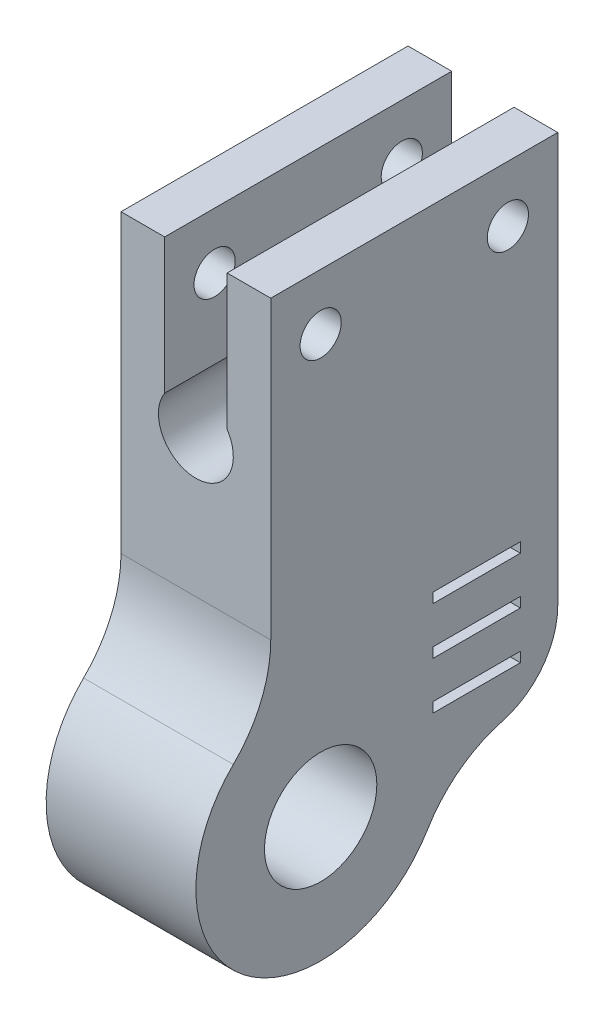
SolidWorks part; units mm, degrees
ref_plane "xy" through (0, 0, 0) normal (0, 0, 1) x (1, 0, 0)
ref_plane "xz" through (0, 0, 0) normal (0, 1, 0) x (1, 0, 0)
ref_plane "yz" through (0, 0, 0) normal (1, 0, 0) x (0, 0, -1)
sketch "Skizze1" plane through (0, 0, 0) normal (1, 0, 0) x (0, 0, -1)
  line L0 (4, 33.8) -> (19, 33.8) construction
  line L1 (13.9955, 0) -> (23, 0)
  line L2 (0, 9.4652) -> (0, 38.3)
  line L3 (0, 38.3) -> (23, 38.3)
  line L4 (23, 0) -> (23, 38.3)
  line L5 (13, 3.8) -> (20, 3.8)
  line L6 (13, 3.8) -> (13, 3)
  line L7 (13, 3) -> (20, 3)
  line L8 (20, 3.8) -> (20, 3)
  line L9 (13, 7.6) -> (20, 7.6)
  line L10 (13, 7.6) -> (13, 6.8)
  line L11 (13, 6.8) -> (20, 6.8)
  line L12 (20, 7.6) -> (20, 6.8)
  line L13 (13, 10.6) -> (20, 10.6)
  line L14 (13, 10.6) -> (13, 11.4)
  line L15 (13, 11.4) -> (20, 11.4)
  line L16 (20, 10.6) -> (20, 11.4)
  line L17 (19, 33.8) -> (11.5, 33.8) construction
  line L18 (11.5, 33.8) -> (11.5, 38.3) construction
  line L19 (0, 25.8) -> (23, 25.8) construction
  line L20 (20, 3.8) -> (20, 6.8) construction
  line L21 (20, 7.6) -> (20, 10.6) construction
  arc A0 (13.9955, 0) -> (0, 9.4652) centre (4, 0.3) cw
  circle A2 centre (4, 33.8) radius 1.65
  circle A3 centre (19, 33.8) radius 1.65
  circle A4 centre (4, 0.3) radius 4.5
  dimension "D9" = 19
  dimension "D2" = 4.5
  dimension "D12" = 3.3
  dimension "D16" = 9
  dimension "D10" = 10
  dimension "D3" = 0.8
  dimension "D4" = 7
  dimension "D5" = 3
  dimension "D6" = 3
  dimension "D7" = 3
  dimension "D8" = 25.5
  dimension "D11" = 23
  dimension "D13" = 22
  dimension "D14" = 15
  dimension "D15" = 8
extrude "Aufsatz-Linear austragen1" add sketch "Skizze1" along normal blind 12
sketch "Skizze2" plane through (0, 0, 0) normal (0, 0, 1) x (1, 0, 0)
  line L0 (12, 38.3) -> (0, 38.3) construction
  line L2 (3.5, 38.3) -> (8.5, 38.3)
  line L4 (3.5, 38.3) -> (3.5, 27.4583)
  line L6 (8.5, 38.3) -> (8.5, 27.4583)
  arc A0 (3.5, 27.4583) -> (8.5, 27.4583) centre (6, 25.8) ccw
  point P4 (6, 38.3)
  dimension "D1" = 6
  dimension "D2" = 5
extrude "Schnitt-Linear austragen2" cut sketch "Skizze2" against normal through all
sketch "Skizze5" plane through (0, 0, 0) normal (1, 0, 0) x (0, 0, -1)
  line L3 (0.1029, 7.05) -> (-3.7942, 0.3)
  line L4 (-3.7942, 0.3) -> (0.1029, -6.45)
  line L5 (0.1029, -6.45) -> (7.8971, -6.45)
  line L6 (7.8971, -6.45) -> (11.7942, 0.3)
  line L7 (11.7942, 0.3) -> (7.8971, 7.05)
  line L8 (7.8971, 7.05) -> (0.1029, 7.05)
  circle A0 centre (4, 0.3) radius 6.75 construction
  dimension "D1" = 13.5
extrude "Schnitt-Linear austragen4" cut sketch "Skizze5" along normal blind 5
fillet "Verrundung1" radius 10 2 edges at (6, 0, -13.9955) (6, 9.4652, 0)
fillet "Verrundung3" radius 6 1 edges at (6, 0, -23)
